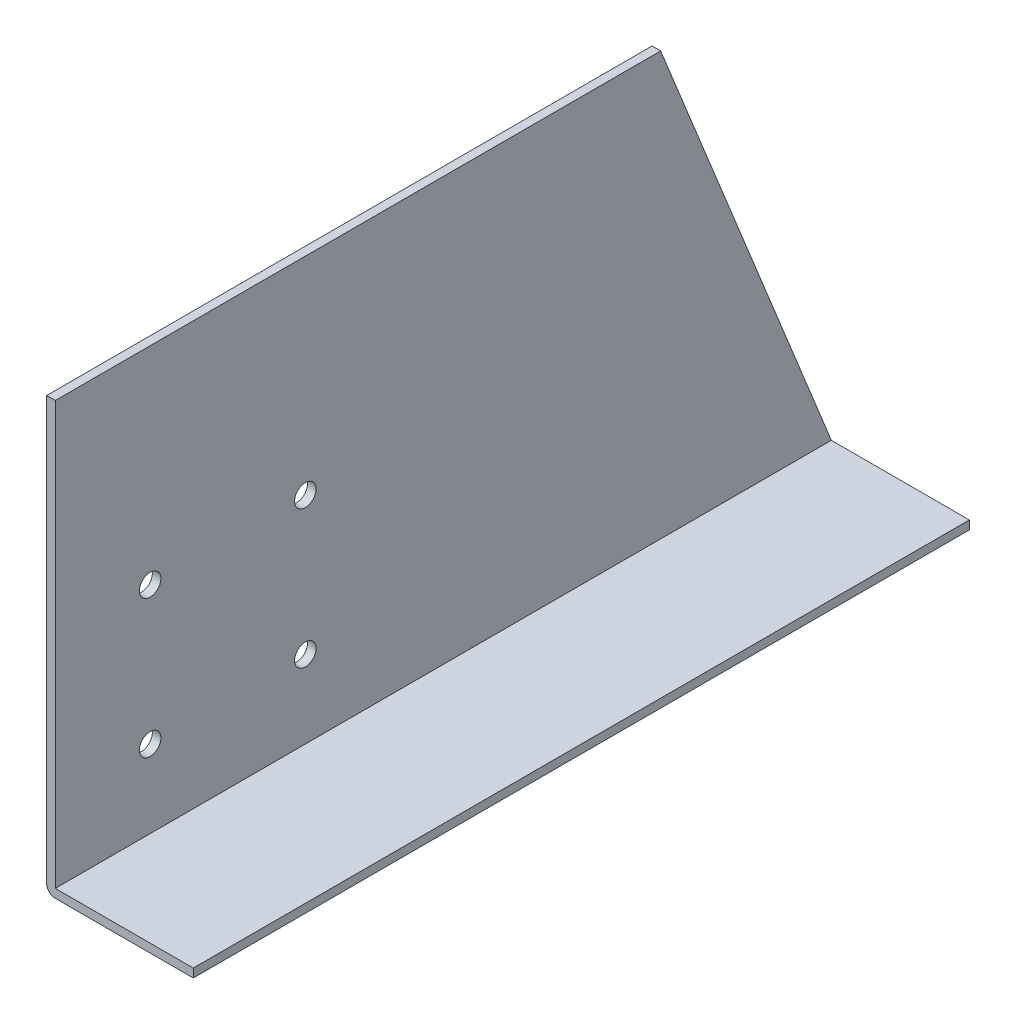
SolidWorks part; units mm, degrees
ref_plane "Front Plane" through (0, 0, 0) normal (0, 0, 1) x (1, 0, 0)
ref_plane "Top Plane" through (0, 0, 0) normal (0, 1, 0) x (1, 0, 0)
ref_plane "Right Plane" through (0, 0, 0) normal (1, 0, 0) x (0, 0, -1)
sketch "Sketch1" plane through (0, 0, 0) normal (0, 0, 1) x (1, 0, 0)
  line L0 (-15, 50) -> (-15, -48)
  line L1 (-17, 50) -> (-15, 50)
  line L2 (-17, 50) -> (-17, -50)
  line L3 (-17, -50) -> (17, -50)
  line L4 (17, -48) -> (17, -50)
  line L5 (-17, 50) -> (17, -50) construction
  line L6 (-17, -50) -> (0, 0) construction
  line L7 (-15, -48) -> (17, -48)
  point P0 (0, 0)
  dimension "D1" = 100
  dimension "D2" = 34
  dimension "D3" = 2
  dimension "D4" = 2
extrude "Boss-Extrude1" add sketch "Sketch1" along normal blind 180
fillet "Fillet1" radius 2 1 edges at (-17, -50, 90)
sketch "Sketch2" plane through (-17, 0, 0) normal (-1, 0, 0) x (0, 0, 1)
  line L0 (0, -48) -> (39.5946, 50)
  line L1 (180, 50) -> (0, 50) construction
  line L2 (39.5946, 50) -> (0, 50)
  line L3 (0, 50) -> (0, -48)
  line L4 (0, -48) -> (180, -48) construction
  line L6 (180, 50) -> (180, -48) construction
  line L7 (140, 22.1429) -> (140, -42.8097) construction
  circle A0 centre (122, 2) radius 2.5
  circle A1 centre (122, -30) radius 2.5
  circle A4 centre (158, -30) radius 2.5
  circle A5 centre (158, 2) radius 2.5
  dimension "D2" = 50
  dimension "D3" = 32
  dimension "D4" = 58
  dimension "D5" = 18
  dimension "D1" = 22
extrude "Cut-Extrude1" cut sketch "Sketch2" against normal blind 180
